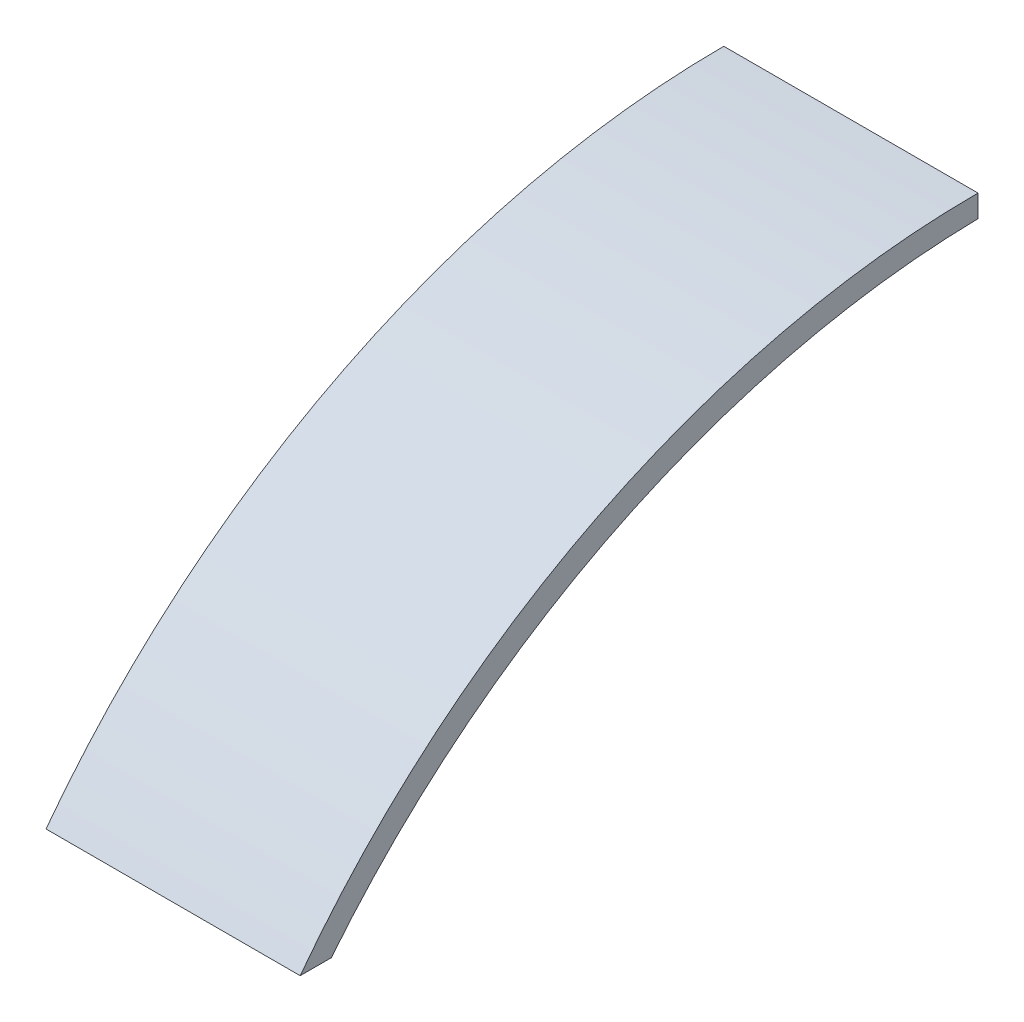
SolidWorks part; units mm, degrees
ref_plane "Front Plane" through (0, 0, 0) normal (0, 0, 1) x (1, 0, 0)
ref_plane "Top Plane" through (0, 0, 0) normal (0, 1, 0) x (1, 0, 0)
ref_plane "Right Plane" through (0, 0, 0) normal (1, 0, 0) x (0, 0, -1)
sketch "Sketch2" plane through (0, 0, 0) normal (1, 0, 0) x (0, 0, -1)
  line L0 (0, 0) -> (914.4, 0) construction
  line L1 (914.4, 0) -> (914.4, 76.2) construction
  line L2 (914.4, 76.2) -> (152.4, 76.2) construction
  line L3 (152.4, 76.2) -> (152.4, 71.2)
  line L4 (0, 0) -> (7, 0)
  arc A0 (0, 0) -> (152.4, 76.2) centre (152.4, -114.3) cw
  arc A1 (7, 0) -> (152.4, 71.2) centre (155.5393, -119.2741) cw
  dimension "D1" = 914.4
  dimension "D2" = 76.2
  dimension "D3" = 762
  dimension "D4" = 5
  dimension "D5" = 7
extrude "Boss-Extrude1" add sketch "Sketch2" along normal blind 57.15 contours A0 L3 A1 L4
